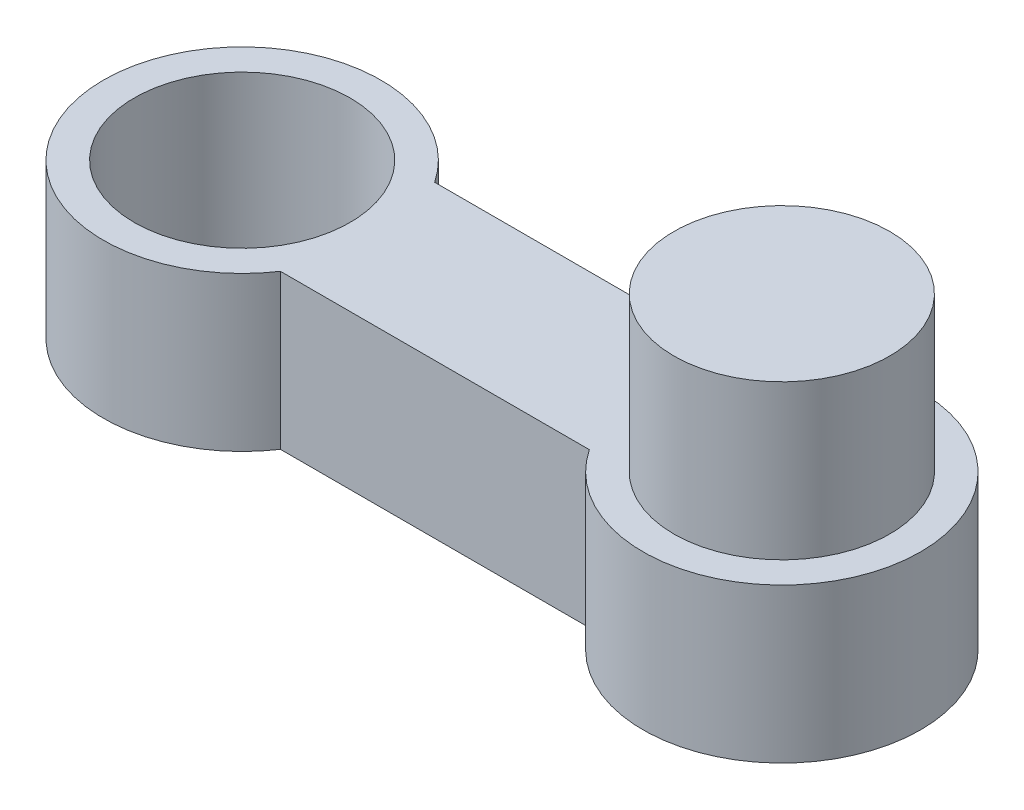
SolidWorks part; units mm, degrees
ref_plane "Front Plane" through (0, 0, 0) normal (0, 0, 1) x (1, 0, 0)
ref_plane "Top Plane" through (0, 0, 0) normal (0, 1, 0) x (1, 0, 0)
ref_plane "Right Plane" through (0, 0, 0) normal (1, 0, 0) x (0, 0, -1)
sketch "Sketch1" plane through (0, 0, 0) normal (0, 1, 0) x (1, 0, 0)
  line L0 (-242.6257, 275.7418) -> (-242.6257, 275.9924)
  line L1 (-242.6257, 175.9924) -> (-42.6257, 175.9924)
  line L2 (-242.6257, 175.9924) -> (-242.6257, 176.2431)
  line L3 (-242.6257, 275.9924) -> (-42.6257, 275.9924)
  line L4 (-42.6257, 175.9924) -> (-42.6257, 176.2431)
  line L5 (-42.6257, 275.7418) -> (-42.6257, 275.9924)
  arc A0 (-242.6257, 275.7418) -> (-242.6257, 176.2431) centre (-317.6257, 225.9924) ccw
  arc A1 (-42.6257, 176.2431) -> (-42.6257, 275.7418) centre (32.3743, 225.9924) ccw
  dimension "D3" = 180
  dimension "D6" = 180
  dimension "D1" = 200
  dimension "D2" = 100
  dimension "D4" = 50
  dimension "D5" = 75
  dimension "D7" = 75
  dimension "D8" = 50
extrude "Boss-Extrude1" add sketch "Sketch1" along normal blind 100
sketch "Sketch2" plane through (0, 100, 0) normal (0, 1, 0) x (1, 0, 0)
  circle A0 centre (-317.6257, 225.9924) radius 70
  dimension "D1" = 140
extrude "Cut-Extrude1" cut sketch "Sketch2" against normal blind 100
sketch "Sketch3" plane through (0, 100, 0) normal (0, 1, 0) x (1, 0, 0)
  circle A0 centre (32.3743, 225.9924) radius 70
  dimension "D1" = 140
extrude "Boss-Extrude2" add sketch "Sketch3" along normal blind 100
ref_point "Point2"
